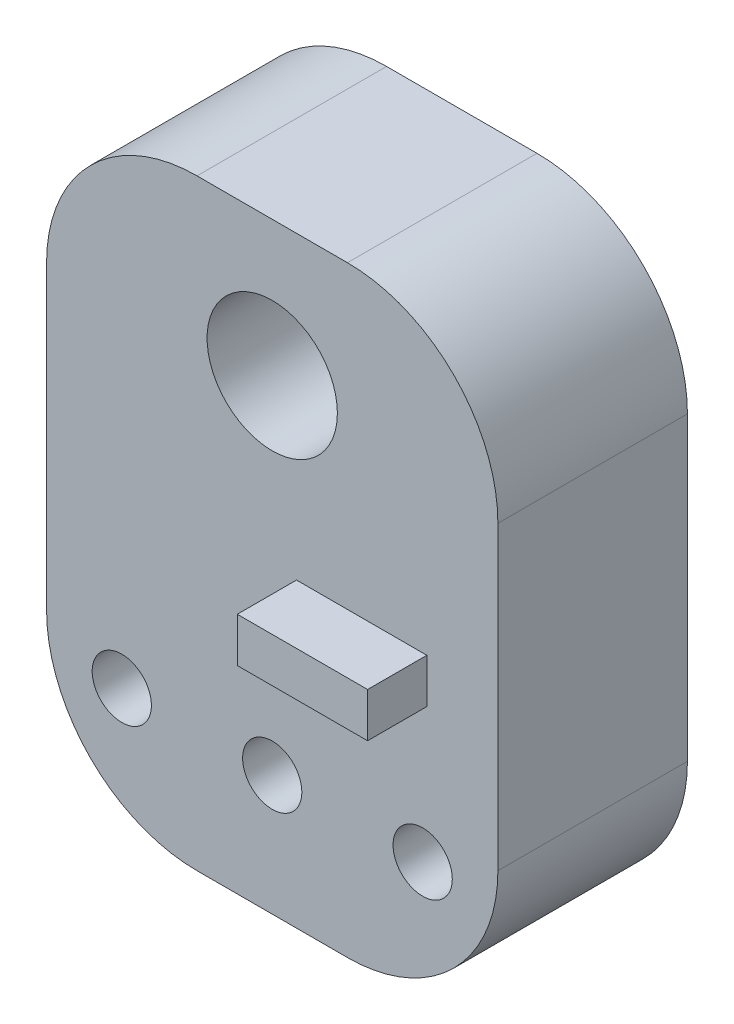
SolidWorks part; units mm, degrees
ref_plane "Plan de face" through (0, 0, 0) normal (0, 0, 1) x (1, 0, 0)
ref_plane "Plan de dessus" through (0, 0, 0) normal (0, 1, 0) x (1, 0, 0)
ref_plane "Plan de droite" through (0, 0, 0) normal (1, 0, 0) x (0, 0, -1)
sketch "Esquisse1" plane through (0, 0, 0) normal (0, 0, 1) x (1, 0, 0)
  line L2 (20.0683, 10.16) -> (22.6083, 10.16)
  line L3 (17.5283, 7.62) -> (17.5283, 2.54)
  line L4 (25.1483, 7.62) -> (25.1483, 2.54)
  line L5 (22.6083, 0) -> (20.0683, 0)
  arc A0 (20.0683, 10.16) -> (17.5283, 7.62) centre (20.0683, 7.62) ccw
  arc A1 (22.6083, 10.16) -> (25.1483, 7.62) centre (22.6083, 7.62) cw
  arc A2 (25.1483, 2.54) -> (22.6083, 0) centre (22.6083, 2.54) cw
  arc A3 (20.0683, 0) -> (17.5283, 2.54) centre (20.0683, 2.54) cw
  circle A4 centre (18.7983, 2.032) radius 0.5
  circle A5 centre (21.3383, 2.032) radius 0.5
  circle A6 centre (23.8783, 2.032) radius 0.5
  circle A7 centre (21.3383, 7.874) radius 1.1
  dimension "D5" = 2.54
  dimension "D6" = 1
  dimension "D9" = 2.2
  dimension "D1" = 1.27
  dimension "D2" = 0.508
  dimension "D3" = 10.16
  dimension "D4" = 7.62
  dimension "D7" = 3.81
  dimension "D8" = 6.35
  dimension "D10" = 3.81
  dimension "D11" = 0.254
extrude "Boss.-Extru.1" add sketch "Esquisse1" along normal blind 3.2
sketch "Esquisse2" plane through (0, 0, 3.2) normal (0, 0, 1) x (1, 0, 0)
  line L1 (21.7483, 5.09) -> (23.9483, 5.09)
  line L2 (21.7483, 5.09) -> (21.7483, 4.34)
  line L3 (21.7483, 4.34) -> (23.9483, 4.34)
  line L4 (23.9483, 5.09) -> (23.9483, 4.34)
  dimension "D1" = 2.2
  dimension "D2" = 0.75
  dimension "D3" = 1.8
  dimension "D4" = 1.2
extrude "Boss.-Extru.2" add sketch "Esquisse2" along normal blind 1
